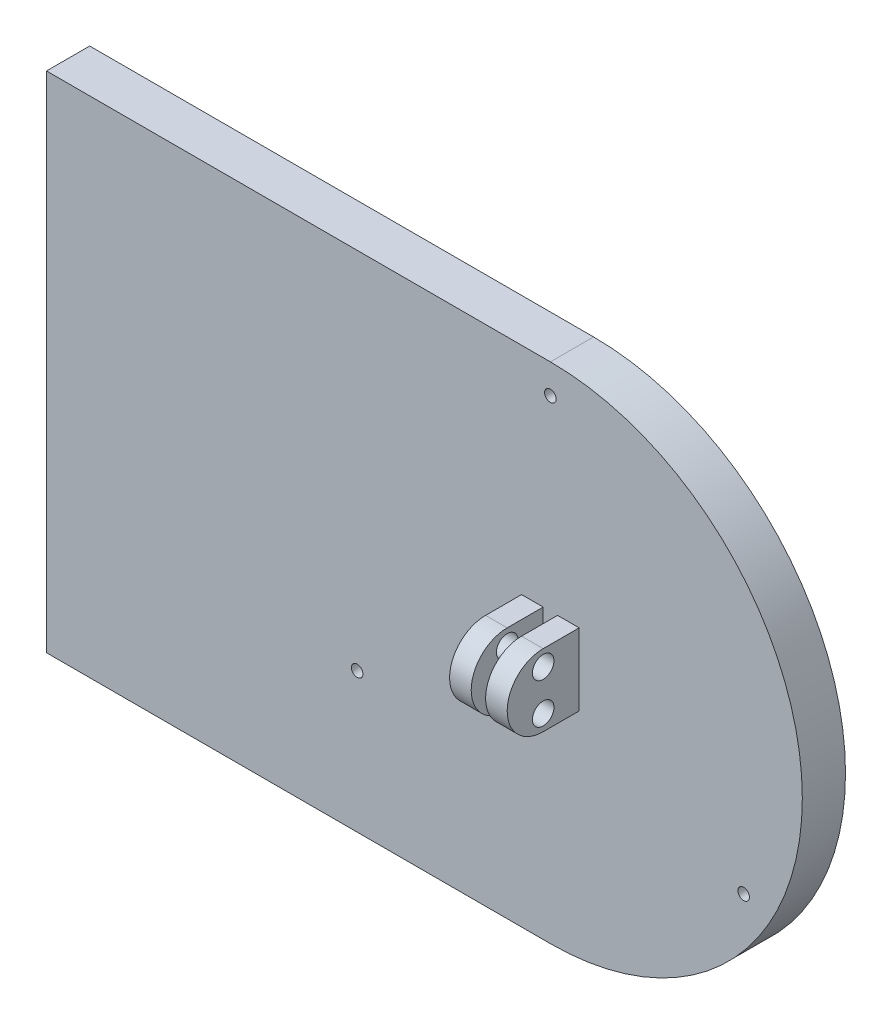
SolidWorks part; units mm, degrees
ref_plane "Front Plane" through (0, 0, 0) normal (0, 0, 1) x (1, 0, 0)
ref_plane "Top Plane" through (0, 0, 0) normal (0, 1, 0) x (1, 0, 0)
ref_plane "Right Plane" through (0, 0, 0) normal (1, 0, 0) x (0, 0, -1)
sketch "Sketch2" plane through (0, 0, 0) normal (0, 0, 1) x (1, 0, 0)
  circle A0 centre (0, 0) radius 35
  point P11 (0, 0)
  dimension "D1" = 70
extrude "Boss-Extrude1" add sketch "Sketch2" along normal blind 6 contours A0
sketch "Sketch8" plane through (0, 0, 0) normal (0, 0, -1) x (-1, 0, 0)
  line L0 (0, 35) -> (0, -35)
  line L1 (0, 35) -> (70, 35)
  line L2 (0, -35) -> (70, -35)
  line L3 (70, 35) -> (70, -35)
  circle A0 centre (0, 0) radius 35 construction
  dimension "D1" = 70
extrude "Boss-Extrude3" add sketch "Sketch8" against normal blind 6
sketch "Sketch3" plane through (0, 0, 6) normal (0, 0, 1) x (1, 0, 0)
  circle A0 centre (0, 30.9143) radius 0.8
  circle A1 centre (26.8468, -15.5857) radius 0.8
  circle A2 centre (-26.8468, -15.5857) radius 0.8
  point P8 (0, -0.0857)
  dimension "D1" = 1.6
  dimension "D3" = 31
  dimension "D2" = 3
extrude "Cut-Extrude1" cut sketch "Sketch3" against normal blind 6
sketch "Sketch4" plane through (0, 0, 6) normal (0, 0, 1) x (1, 0, 0)
  circle A0 centre (0, 0) radius 0.6
  dimension "D1" = 1.2
extrude "Cut-Extrude2" cut sketch "Sketch4" against normal blind 6
sketch "Sketch5" plane through (0, 0, 6) normal (0, 0, 1) x (1, 0, 0)
  line L1 (1, 5) -> (4, 5)
  line L2 (1, 5) -> (1, -5)
  line L3 (1, -5) -> (4, -5)
  line L4 (4, 5) -> (4, -5)
  line L5 (-1, 5) -> (-4, 5)
  line L6 (-1, 5) -> (-1, -5)
  line L7 (-1, -5) -> (-4, -5)
  line L8 (-4, 5) -> (-4, -5)
  dimension "D1" = 10
  dimension "D2" = 3
  dimension "D3" = 4
  dimension "D4" = 5
  dimension "D5" = 4
  dimension "D6" = 5
extrude "Boss-Extrude2" add sketch "Sketch5" along normal blind 10
sketch "Sketch6" plane through (4, 0, 0) normal (1, 0, 0) x (0, 0, -1)
  line L1 (-16, 5) -> (-6, 5) construction
  line L2 (-11, 5) -> (-16, 5)
  line L3 (-16, 5) -> (-16, -5)
  line L5 (-16, -5) -> (-11, -5)
  line L6 (-16, 5) -> (-11, 5)
  arc A2 (-11, -5) -> (-11, 5) centre (-11, 0) cw
  line M5 (-6, 5) -> (-16, 5)
  line M6 (-16, 5) -> (-16, -5)
  line M7 (-16, -5) -> (-6, -5)
extrude "Cut-Extrude3" cut sketch "Sketch6" against normal through all contours A2 M6 M5 | A2 L3 M7
sketch "Sketch7" plane through (4, 0, 0) normal (1, 0, 0) x (0, 0, -1)
  line L1 (-11, 5) -> (-6, 5) construction
  line L2 (-11, -5) -> (-6, -5) construction
  circle A2 centre (-11, 2.8) radius 1.5
  circle A3 centre (-11, -2.8) radius 1.5
  dimension "D1" = 2.2
  dimension "D2" = 2.2
  dimension "D4" = 3
extrude "Cut-Extrude4" cut sketch "Sketch7" against normal through all
